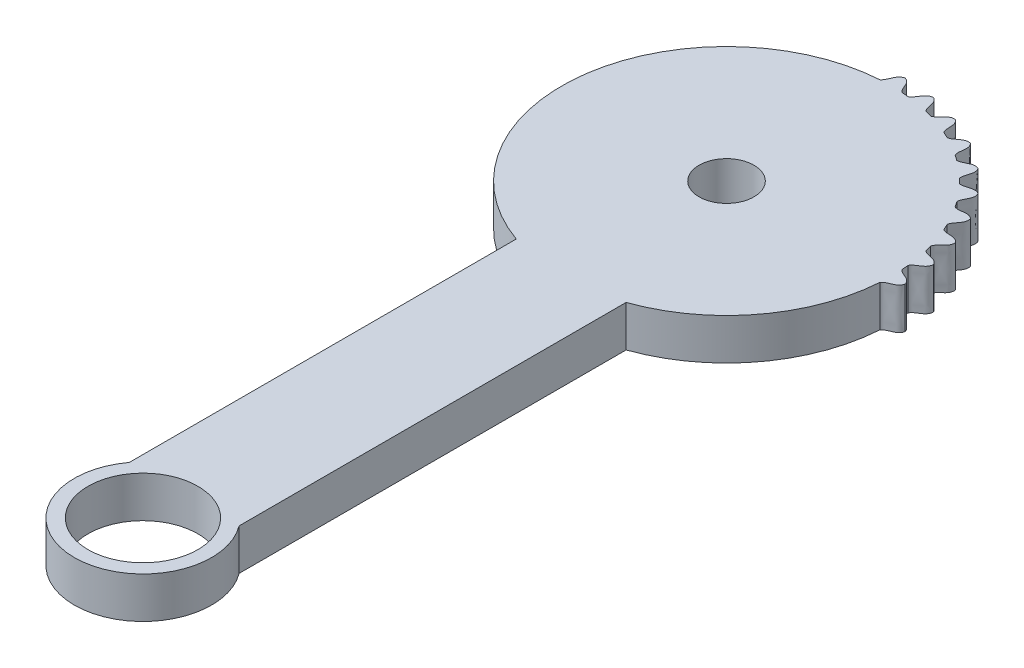
SolidWorks part; units mm, degrees
ref_plane "前视基准面" through (0, 0, 0) normal (0, 0, 1) x (1, 0, 0)
ref_plane "上视基准面" through (0, 0, 0) normal (0, 1, 0) x (1, 0, 0)
ref_plane "右视基准面" through (0, 0, 0) normal (1, 0, 0) x (0, 0, -1)
sketch "草图1" plane through (0, 0, 0) normal (0, 1, 0) x (1, 0, 0)
  line L0 (0, 0) -> (0, 12) construction
  line L1 (0, 12) -> (0, 13) construction
  line L2 (0, 13) -> (0, 50000) construction
  arc A0 (-0.8042, 11.973) -> (11.973, -0.8042) centre (0, 0) ccw
  circle A1 centre (0, 0) radius 13 construction
  arc A2 (0, 12) -> (-0.8042, 11.973) centre (0, 0) ccw construction
  arc A3 (0.8042, 11.973) -> (0, 12) centre (0, 0) ccw construction
  arc A4 (2.871, 11.6515) -> (1.2871, 11.9308) centre (0, 0) ccw construction
  arc A5 (1.2871, 11.9308) -> (0.8042, 11.973) centre (0, 0) ccw
  arc A6 (4.8507, 10.9759) -> (3.3393, 11.526) centre (0, 0) ccw construction
  arc A7 (3.3393, 11.526) -> (2.871, 11.6515) centre (0, 0) ccw
  arc A8 (6.6829, 9.9669) -> (5.2901, 10.771) centre (0, 0) ccw construction
  arc A9 (5.2901, 10.771) -> (4.8507, 10.9759) centre (0, 0) ccw
  arc A10 (10.771, 5.2901) -> (9.9669, 6.6829) centre (0, 0) ccw construction
  arc A11 (9.9669, 6.6829) -> (9.6888, 7.0801) centre (0, 0) ccw
  arc A12 (11.526, 3.3393) -> (10.9759, 4.8507) centre (0, 0) ccw construction
  arc A13 (10.9759, 4.8507) -> (10.771, 5.2901) centre (0, 0) ccw
  arc A14 (11.9308, 1.2871) -> (11.6515, 2.871) centre (0, 0) ccw construction
  arc A15 (11.6515, 2.871) -> (11.526, 3.3393) centre (0, 0) ccw
  arc A16 (11.973, -0.8042) -> (11.973, 0.8042) centre (0, 0) ccw construction
  arc A17 (11.973, 0.8042) -> (11.9308, 1.2871) centre (0, 0) ccw
  arc A18 (7.0801, 9.6888) -> (6.6829, 9.9669) centre (0, 0) ccw
  arc A19 (8.655, 8.3121) -> (8.3121, 8.655) centre (0, 0) ccw
  circle A20 centre (0, 0) radius 2
  spline S0 degree 3 poles (0, 13) (-0.3118, 12.9233) (-0.4918, 12.4956) (-0.6603, 12.0828) (-0.8042, 11.973) knots 0 0 0 0 0.615003 1 1 1 1
  spline S1 degree 3 poles (0, 13) (0.3118, 12.9233) (0.4918, 12.4956) (0.6603, 12.0828) (0.8042, 11.973) knots 0 0 0 0 0.615003 1 1 1 1
  spline S2 degree 3 poles (2.2574, 12.8025) (1.937, 12.7811) (1.6856, 12.3911) (1.4479, 12.0139) (1.2871, 11.9308) knots 0 0 0 0 0.615003 1 1 1 1
  spline S3 degree 3 poles (2.2574, 12.8025) (2.5512, 12.6728) (2.6541, 12.2203) (2.7484, 11.7845) (2.871, 11.6515) knots 0 0 0 0 0.615003 1 1 1 1
  spline S4 degree 3 poles (4.4463, 12.216) (4.127, 12.2506) (3.8116, 11.9102) (3.5121, 11.5799) (3.3393, 11.526) knots 0 0 0 0 0.615003 1 1 1 1
  spline S5 degree 3 poles (4.4463, 12.216) (4.713, 12.0373) (4.7358, 11.5738) (4.753, 11.1283) (4.8507, 10.9759) knots 0 0 0 0 0.615003 1 1 1 1
  spline S6 degree 3 poles (6.5, 11.2583) (6.1916, 11.3478) (5.8219, 11.0674) (5.4696, 10.7941) (5.2901, 10.771) knots 0 0 0 0 0.615003 1 1 1 1
  spline S7 degree 3 poles (6.5, 11.2583) (6.7317, 11.036) (6.6737, 10.5756) (6.6132, 10.1338) (6.6829, 9.9669) knots 0 0 0 0 0.615003 1 1 1 1
  spline S8 degree 3 poles (8.3562, 9.9586) (8.0681, 10.1002) (7.6553, 9.8883) (7.2608, 9.6804) (7.0801, 9.6888) knots 0 0 0 0 0.615003 1 1 1 1
  spline S9 degree 3 poles (8.3562, 9.9586) (8.5458, 9.6994) (8.4087, 9.2561) (8.2725, 8.8315) (8.3121, 8.655) knots 0 0 0 0 0.615003 1 1 1 1
  spline S10 degree 3 poles (9.9586, 8.3562) (9.6994, 8.5458) (9.2561, 8.4087) (8.8315, 8.2725) (8.655, 8.3121) knots 0 0 0 0 0.615003 1 1 1 1
  spline S11 degree 3 poles (9.9586, 8.3562) (10.1002, 8.0681) (9.8883, 7.6553) (9.6804, 7.2608) (9.6888, 7.0801) knots 0 0 0 0 0.615003 1 1 1 1
  spline S12 degree 3 poles (11.2583, 6.5) (11.036, 6.7317) (10.5756, 6.6737) (10.1338, 6.6132) (9.9669, 6.6829) knots 0 0 0 0 0.615003 1 1 1 1
  spline S13 degree 3 poles (11.2583, 6.5) (11.3478, 6.1916) (11.0674, 5.8219) (10.7941, 5.4696) (10.771, 5.2901) knots 0 0 0 0 0.615003 1 1 1 1
  spline S14 degree 3 poles (12.216, 4.4463) (12.0373, 4.713) (11.5738, 4.7358) (11.1283, 4.753) (10.9759, 4.8507) knots 0 0 0 0 0.615003 1 1 1 1
  spline S15 degree 3 poles (12.216, 4.4463) (12.2506, 4.127) (11.9102, 3.8116) (11.5799, 3.5121) (11.526, 3.3393) knots 0 0 0 0 0.615003 1 1 1 1
  spline S16 degree 3 poles (12.8025, 2.2574) (12.6728, 2.5512) (12.2203, 2.6541) (11.7845, 2.7484) (11.6515, 2.871) knots 0 0 0 0 0.615003 1 1 1 1
  spline S17 degree 3 poles (12.8025, 2.2574) (12.7811, 1.937) (12.3911, 1.6856) (12.0139, 1.4479) (11.9308, 1.2871) knots 0 0 0 0 0.615003 1 1 1 1
  spline S18 degree 3 poles (13, 0) (12.9233, 0.3118) (12.4956, 0.4918) (12.0828, 0.6603) (11.973, 0.8042) knots 0 0 0 0 0.615003 1 1 1 1
  spline S19 degree 3 poles (13, 0) (12.9233, -0.3118) (12.4956, -0.4918) (12.0828, -0.6603) (11.973, -0.8042) knots 0 0 0 0 0.615003 1 1 1 1
  point P98 (0, 0)
  dimension "D1" = 24
  dimension "D2" = 26
  dimension "D3" = 4
extrude "凸台-拉伸1" add sketch "草图1" along normal blind 3 contours S19 S18 A17 S17 S16 A15 S15 S14 A13 S13 S12 A11 S7 S6 A9 S5 S4 A7 S3 S2 A5 S1 S0 A0
sketch "草图2" plane through (0, 3, 0) normal (0, 1, 0) x (1, 0, 0)
  line L0 (0, 0) -> (0, -50000) construction
  line L1 (-4, -11.3137) -> (-4, -39.5)
  line L2 (-4, -39.5) -> (4, -39.5)
  line L3 (4, -39.5) -> (4, -11.3137)
  arc A0 (-0.8042, 11.973) -> (11.973, -0.8042) centre (0, 0) ccw construction
  arc A1 (-4, -11.3137) -> (4, -11.3137) centre (0, 0) ccw
  circle A2 centre (0, -42.5) radius 5
  circle A3 centre (0, -42.5) radius 4
  arc M30 (-0.8042, 11.973) -> (11.973, -0.8042) centre (0, 0) ccw
  dimension "D2" = 10
  dimension "D4" = 8
  dimension "D1" = 39.5
  dimension "D3" = 8
extrude "凸台-拉伸2" add sketch "草图2" against normal blind 3 contours A1 L0 A2 L3 | L0 L1 A2 M30 | A3 L0 A2 L2 | A2 L0 A3 L2 | L0 A2 L2 A3 | L0 A3 L2 A2
